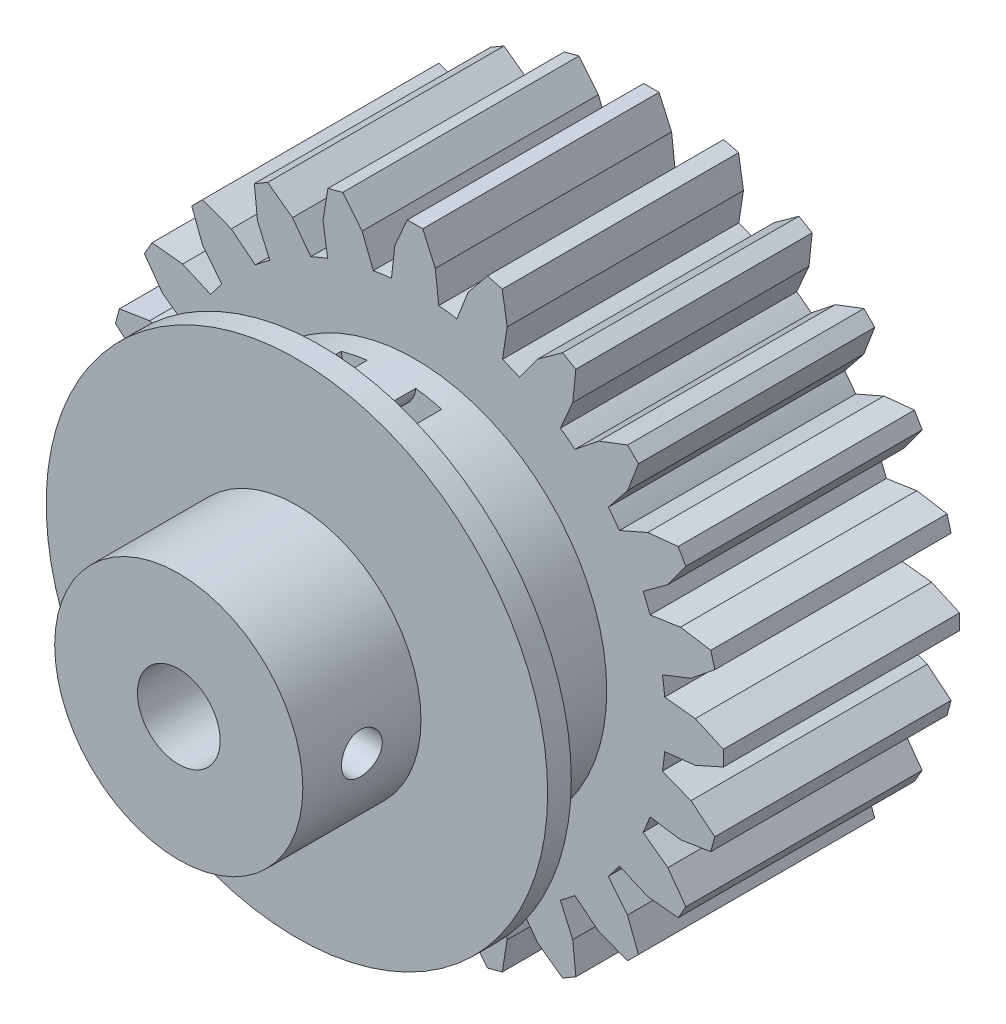
SolidWorks part; units mm, degrees
ref_plane "Plan de face" through (0, 0, 0) normal (0, 0, 1) x (1, 0, 0)
ref_plane "Plan de dessus" through (0, 0, 0) normal (0, 1, 0) x (1, 0, 0)
ref_plane "Plan de droite" through (0, 0, 0) normal (1, 0, 0) x (0, 0, -1)
sketch "Esquisse1" plane through (0, 0, 0) normal (0, 0, 1) x (1, 0, 0)
  line L0 (-2, 21.1255) -> (-1.7102, 23.7093)
  line L1 (0, 2.2889) -> (0, 19223.5431) construction
  line L2 (-1.7102, 23.7093) -> (-0.65, 26.0834)
  line L3 (-0.65, 26.0834) -> (0.65, 26.0834)
  line L4 (0, 0) -> (50000, 0) construction
  line L5 (2, 21.1255) -> (1.7102, 23.7093)
  line L6 (1.7102, 23.7093) -> (0.65, 26.0834)
  line L7 (3.5358, 20.9233) -> (4.4845, 23.3441)
  line L8 (4.4845, 23.3441) -> (6.123, 25.3628)
  line L9 (7.7883, 22.4588) -> (7.3787, 25.0264)
  line L10 (7.3995, 19.8881) -> (7.7883, 22.4588)
  line L11 (6.123, 25.3628) -> (7.3787, 25.0264)
  line L12 (8.8307, 19.2953) -> (10.3736, 21.388)
  line L13 (10.3736, 21.388) -> (12.4788, 22.9139)
  line L14 (13.3357, 19.6778) -> (13.6046, 22.2639)
  line L15 (12.2948, 17.2953) -> (13.3357, 19.6778)
  line L16 (12.4788, 22.9139) -> (13.6046, 22.2639)
  line L17 (13.5238, 16.3522) -> (15.5558, 17.9743)
  line L18 (15.5558, 17.9743) -> (17.9841, 18.9033)
  line L19 (17.9743, 15.5558) -> (18.9033, 17.9841)
  line L20 (16.3522, 13.5238) -> (17.9743, 15.5558)
  line L21 (17.9841, 18.9033) -> (18.9033, 17.9841)
  line L22 (17.2953, 12.2948) -> (19.6778, 13.3357)
  line L23 (19.6778, 13.3357) -> (22.2639, 13.6046)
  line L24 (21.388, 10.3736) -> (22.9139, 12.4788)
  line L25 (19.2953, 8.8307) -> (21.388, 10.3736)
  line L26 (22.2639, 13.6046) -> (22.9139, 12.4788)
  line L27 (19.8881, 7.3995) -> (22.4588, 7.7883)
  line L28 (22.4588, 7.7883) -> (25.0264, 7.3787)
  line L29 (23.3441, 4.4845) -> (25.3628, 6.123)
  line L30 (20.9233, 3.5358) -> (23.3441, 4.4845)
  line L31 (25.0264, 7.3787) -> (25.3628, 6.123)
  line L32 (21.1255, 2) -> (23.7093, 1.7102)
  line L33 (23.7093, 1.7102) -> (26.0834, 0.65)
  line L34 (23.7093, -1.7102) -> (26.0834, -0.65)
  line L35 (21.1255, -2) -> (23.7093, -1.7102)
  line L36 (26.0834, 0.65) -> (26.0834, -0.65)
  line L37 (20.9233, -3.5358) -> (23.3441, -4.4845)
  line L38 (23.3441, -4.4845) -> (25.3628, -6.123)
  line L39 (22.4588, -7.7883) -> (25.0264, -7.3787)
  line L40 (19.8881, -7.3995) -> (22.4588, -7.7883)
  line L41 (25.3628, -6.123) -> (25.0264, -7.3787)
  line L42 (19.2953, -8.8307) -> (21.388, -10.3736)
  line L43 (21.388, -10.3736) -> (22.9139, -12.4788)
  line L44 (19.6778, -13.3357) -> (22.2639, -13.6046)
  line L45 (17.2953, -12.2948) -> (19.6778, -13.3357)
  line L46 (22.9139, -12.4788) -> (22.2639, -13.6046)
  line L47 (16.3522, -13.5238) -> (17.9743, -15.5558)
  line L48 (17.9743, -15.5558) -> (18.9033, -17.9841)
  line L49 (15.5558, -17.9743) -> (17.9841, -18.9033)
  line L50 (13.5238, -16.3522) -> (15.5558, -17.9743)
  line L51 (18.9033, -17.9841) -> (17.9841, -18.9033)
  line L52 (12.2948, -17.2953) -> (13.3357, -19.6778)
  line L53 (13.3357, -19.6778) -> (13.6046, -22.2639)
  line L54 (10.3736, -21.388) -> (12.4788, -22.9139)
  line L55 (8.8307, -19.2953) -> (10.3736, -21.388)
  line L56 (13.6046, -22.2639) -> (12.4788, -22.9139)
  line L57 (7.3995, -19.8881) -> (7.7883, -22.4588)
  line L58 (7.7883, -22.4588) -> (7.3787, -25.0264)
  line L59 (4.4845, -23.3441) -> (6.123, -25.3628)
  line L60 (3.5358, -20.9233) -> (4.4845, -23.3441)
  line L61 (7.3787, -25.0264) -> (6.123, -25.3628)
  line L62 (2, -21.1255) -> (1.7102, -23.7093)
  line L63 (1.7102, -23.7093) -> (0.65, -26.0834)
  line L64 (-1.7102, -23.7093) -> (-0.65, -26.0834)
  line L65 (-2, -21.1255) -> (-1.7102, -23.7093)
  line L66 (0.65, -26.0834) -> (-0.65, -26.0834)
  line L67 (-3.5358, -20.9233) -> (-4.4845, -23.3441)
  line L68 (-4.4845, -23.3441) -> (-6.123, -25.3628)
  line L69 (-7.7883, -22.4588) -> (-7.3787, -25.0264)
  line L70 (-7.3995, -19.8881) -> (-7.7883, -22.4588)
  line L71 (-6.123, -25.3628) -> (-7.3787, -25.0264)
  line L72 (-8.8307, -19.2953) -> (-10.3736, -21.388)
  line L73 (-10.3736, -21.388) -> (-12.4788, -22.9139)
  line L74 (-13.3357, -19.6778) -> (-13.6046, -22.2639)
  line L75 (-12.2948, -17.2953) -> (-13.3357, -19.6778)
  line L76 (-12.4788, -22.9139) -> (-13.6046, -22.2639)
  line L77 (-13.5238, -16.3522) -> (-15.5558, -17.9743)
  line L78 (-15.5558, -17.9743) -> (-17.9841, -18.9033)
  line L79 (-17.9743, -15.5558) -> (-18.9033, -17.9841)
  line L80 (-16.3522, -13.5238) -> (-17.9743, -15.5558)
  line L81 (-17.9841, -18.9033) -> (-18.9033, -17.9841)
  line L82 (-17.2953, -12.2948) -> (-19.6778, -13.3357)
  line L83 (-19.6778, -13.3357) -> (-22.2639, -13.6046)
  line L84 (-21.388, -10.3736) -> (-22.9139, -12.4788)
  line L85 (-19.2953, -8.8307) -> (-21.388, -10.3736)
  line L86 (-22.2639, -13.6046) -> (-22.9139, -12.4788)
  line L87 (-19.8881, -7.3995) -> (-22.4588, -7.7883)
  line L88 (-22.4588, -7.7883) -> (-25.0264, -7.3787)
  line L89 (-23.3441, -4.4845) -> (-25.3628, -6.123)
  line L90 (-20.9233, -3.5358) -> (-23.3441, -4.4845)
  line L91 (-25.0264, -7.3787) -> (-25.3628, -6.123)
  line L92 (-21.1255, -2) -> (-23.7093, -1.7102)
  line L93 (-23.7093, -1.7102) -> (-26.0834, -0.65)
  line L94 (-23.7093, 1.7102) -> (-26.0834, 0.65)
  line L95 (-21.1255, 2) -> (-23.7093, 1.7102)
  line L96 (-26.0834, -0.65) -> (-26.0834, 0.65)
  line L97 (-20.9233, 3.5358) -> (-23.3441, 4.4845)
  line L98 (-23.3441, 4.4845) -> (-25.3628, 6.123)
  line L99 (-22.4588, 7.7883) -> (-25.0264, 7.3787)
  line L100 (-19.8881, 7.3995) -> (-22.4588, 7.7883)
  line L101 (-25.3628, 6.123) -> (-25.0264, 7.3787)
  line L102 (-19.2953, 8.8307) -> (-21.388, 10.3736)
  line L103 (-21.388, 10.3736) -> (-22.9139, 12.4788)
  line L104 (-19.6778, 13.3357) -> (-22.2639, 13.6046)
  line L105 (-17.2953, 12.2948) -> (-19.6778, 13.3357)
  line L106 (-22.9139, 12.4788) -> (-22.2639, 13.6046)
  line L107 (-16.3522, 13.5238) -> (-17.9743, 15.5558)
  line L108 (-17.9743, 15.5558) -> (-18.9033, 17.9841)
  line L109 (-15.5558, 17.9743) -> (-17.9841, 18.9033)
  line L110 (-13.5238, 16.3522) -> (-15.5558, 17.9743)
  line L111 (-18.9033, 17.9841) -> (-17.9841, 18.9033)
  line L112 (-12.2948, 17.2953) -> (-13.3357, 19.6778)
  line L113 (-13.3357, 19.6778) -> (-13.6046, 22.2639)
  line L114 (-10.3736, 21.388) -> (-12.4788, 22.9139)
  line L115 (-8.8307, 19.2953) -> (-10.3736, 21.388)
  line L116 (-13.6046, 22.2639) -> (-12.4788, 22.9139)
  line L117 (-7.3995, 19.8881) -> (-7.7883, 22.4588)
  line L118 (-7.7883, 22.4588) -> (-7.3787, 25.0264)
  line L119 (-4.4845, 23.3441) -> (-6.123, 25.3628)
  line L120 (-3.5358, 20.9233) -> (-4.4845, 23.3441)
  line L121 (-7.3787, 25.0264) -> (-6.123, 25.3628)
  arc A0 (-7.3995, 19.8881) -> (-8.8307, 19.2953) centre (0, 0) ccw
  circle A1 centre (0, 0) radius 3.5
  arc A2 (-2, 21.1255) -> (-3.5358, 20.9233) centre (0, 0) ccw
  arc A3 (3.5358, 20.9233) -> (2, 21.1255) centre (0, 0) ccw
  arc A4 (8.8307, 19.2953) -> (7.3995, 19.8881) centre (0, 0) ccw
  arc A5 (13.5238, 16.3522) -> (12.2948, 17.2953) centre (0, 0) ccw
  arc A6 (17.2953, 12.2948) -> (16.3522, 13.5238) centre (0, 0) ccw
  arc A7 (19.8881, 7.3995) -> (19.2953, 8.8307) centre (0, 0) ccw
  arc A8 (21.1255, 2) -> (20.9233, 3.5358) centre (0, 0) ccw
  arc A9 (20.9233, -3.5358) -> (21.1255, -2) centre (0, 0) ccw
  arc A10 (19.2953, -8.8307) -> (19.8881, -7.3995) centre (0, 0) ccw
  arc A11 (16.3522, -13.5238) -> (17.2953, -12.2948) centre (0, 0) ccw
  arc A12 (12.2948, -17.2953) -> (13.5238, -16.3522) centre (0, 0) ccw
  arc A13 (7.3995, -19.8881) -> (8.8307, -19.2953) centre (0, 0) ccw
  arc A14 (2, -21.1255) -> (3.5358, -20.9233) centre (0, 0) ccw
  arc A15 (-3.5358, -20.9233) -> (-2, -21.1255) centre (0, 0) ccw
  arc A16 (-8.8307, -19.2953) -> (-7.3995, -19.8881) centre (0, 0) ccw
  arc A17 (-13.5238, -16.3522) -> (-12.2948, -17.2953) centre (0, 0) ccw
  arc A18 (-17.2953, -12.2948) -> (-16.3522, -13.5238) centre (0, 0) ccw
  arc A19 (-19.8881, -7.3995) -> (-19.2953, -8.8307) centre (0, 0) ccw
  arc A20 (-21.1255, -2) -> (-20.9233, -3.5358) centre (0, 0) ccw
  arc A21 (-20.9233, 3.5358) -> (-21.1255, 2) centre (0, 0) ccw
  arc A22 (-19.2953, 8.8307) -> (-19.8881, 7.3995) centre (0, 0) ccw
  arc A23 (-16.3522, 13.5238) -> (-17.2953, 12.2948) centre (0, 0) ccw
  arc A24 (-12.2948, 17.2953) -> (-13.5238, 16.3522) centre (0, 0) ccw
  point P17 (0, 26.0834)
  point P156 (0, 0)
  dimension "D1" = 42.44
  dimension "D2" = 7
  dimension "D3" = 2.6
  dimension "D4" = 83.6
  dimension "D5" = 2
  dimension "D6" = 2.6
  dimension "D7" = 0.65
  dimension "D8" = 24
extrude "Boss.-Extru.1" add sketch "Esquisse1" along normal blind 20
sketch "Esquisse2" plane through (0, 0, 20) normal (0, 0, 1) x (1, 0, 0)
  circle A0 centre (0, 0) radius 3.5
  circle A1 centre (0, 0) radius 16.22
  circle A2 centre (0, 0) radius 3.5 construction
  arc A3 (-2, 21.1255) -> (-3.5358, 20.9233) centre (0, 0) ccw construction
  dimension "D1" = 5
extrude "Boss.-Extru.2" add sketch "Esquisse2" along normal blind 10
sketch "Esquisse14" plane through (0, 0, 30) normal (0, 0, 1) x (1, 0, 0)
  circle A0 centre (0, 0) radius 3.5
  circle A1 centre (0, 0) radius 10.5
  dimension "D1" = 7
extrude "Boss.-Extru.9" add sketch "Esquisse14" along normal blind 10
sketch "Esquisse15" plane through (0, 0, 30) normal (0, 0, 1) x (1, 0, 0)
  circle A0 centre (0, 0) radius 16.22
  circle A2 centre (0, 0) radius 21.22
  circle A3 centre (0, 0) radius 16.22 construction
  arc A4 (-12.2948, 17.2953) -> (-13.5238, 16.3522) centre (0, 0) ccw construction
extrude "Boss.-Extru.10" add sketch "Esquisse15" against normal blind 2
sketch "Esquisse3" plane through (0, 0, 0) normal (1, 0, 0) x (0, -1, 0)
  line L0 (-7.5, -35) -> (49992.5, -35) construction
  line L1 (-10.5, -30) -> (10.5, -30) construction
  line L2 (0, -30) -> (0, 49970) construction
  line L3 (-16.22, -30) -> (16.22, -30) construction
  line L4 (-10.5, -40) -> (10.5, -40) construction
  circle A0 centre (0, -35) radius 1.725
  point P13 (0, -30)
  dimension "D1" = 3.45
extrude "Enlèv. mat.-Extru.1" cut sketch "Esquisse3" along normal up to surface (10.5 mm away) up to face at (10.5, 0, 40)
sketch "Esquisse16" plane through (0, 0, 20) normal (0, 0, 1) x (1, 0, 0)
  line L0 (0, 0) -> (0, 50000) construction
  arc A0 (-2.054, 16.0894) -> (2.054, 16.0894) centre (0, 16.22) ccw
  circle A1 centre (0, 0) radius 16.22 construction
  arc A2 (-4.252, 15.6528) -> (4.252, 15.6528) centre (0, 16.22) ccw
  arc A5 (-2.054, 16.0894) -> (-4.252, 15.6528) centre (-2.8834, 14.5139) ccw
  arc A6 (4.252, 15.6528) -> (2.054, 16.0894) centre (2.7192, 13.6875) ccw
  point P12 (0, 0)
  point P13 (1.9489, 16.1025)
  point P14 (4.3344, 15.6301)
  point P15 (-2.0313, 16.0923)
  point P16 (-4.252, 15.6528)
extrude "Enlèv. mat.-Extru.2" cut sketch "Esquisse16" along normal offset from surface (4 mm away) 2 from offset 2 up to face at (16.22, 0, 28)
equation "\"L\"= 20cm'Longueur de tensionnement"
